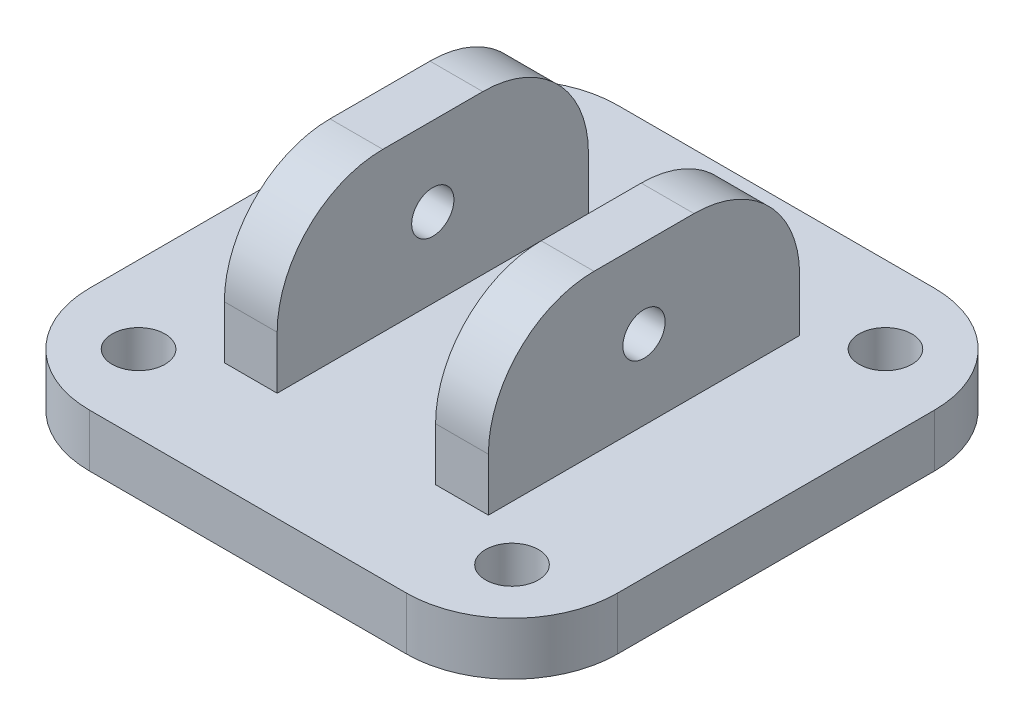
SolidWorks part; units mm, degrees
ref_plane "Front Plane" through (0, 0, 0) normal (0, 0, 1) x (1, 0, 0)
ref_plane "Top Plane" through (0, 0, 0) normal (0, 1, 0) x (1, 0, 0)
ref_plane "Right Plane" through (0, 0, 0) normal (1, 0, 0) x (0, 0, -1)
sketch "Sketch1" plane through (0, 0, 0) normal (0, 1, 0) x (1, 0, 0)
  line L0 (0, 0) -> (-17.68, 0) construction
  line L1 (-17.68, -17.68) -> (17.68, -17.68) construction
  line L2 (-17.68, -17.68) -> (-17.68, 17.68) construction
  line L3 (-17.68, 17.68) -> (17.68, 17.68) construction
  line L4 (17.68, -17.68) -> (17.68, 17.68) construction
  line L5 (-17.68, -17.68) -> (17.68, 17.68) construction
  line L6 (-17.68, 17.68) -> (17.68, -17.68) construction
  line L8 (-25, -25) -> (25, -25)
  line L9 (-25, -25) -> (-25, 25)
  line L10 (-25, 25) -> (25, 25)
  line L11 (25, -25) -> (25, 25)
  line L12 (-25, -25) -> (25, 25) construction
  line L13 (-25, 25) -> (25, -25) construction
  circle A0 centre (-17.68, 17.68) radius 2.5
  circle A1 centre (17.68, 17.68) radius 2.5
  circle A2 centre (17.68, -17.68) radius 2.5
  circle A3 centre (-17.68, -17.68) radius 2.5
  point P0 (0, 0)
  dimension "D3" = 5
  dimension "D4" = 5
  dimension "D1" = 35.36
  dimension "D2" = 35.36
  dimension "D5" = 50
  dimension "D6" = 50
extrude "Boss-Extrude1" add sketch "Sketch1" along normal blind 5
sketch "Sketch2" plane through (0, 5, 0) normal (0, 1, 0) x (1, 0, 0)
  line L1 (-12.5, -14.7343) -> (12.5, -14.7343)
  line L2 (-12.5, -14.7343) -> (-12.5, 14.7343)
  line L3 (-12.5, 14.7343) -> (12.5, 14.7343)
  line L4 (12.5, -14.7343) -> (12.5, 14.7343)
  line L5 (-12.5, -14.7343) -> (12.5, 14.7343) construction
  line L6 (-12.5, 14.7343) -> (12.5, -14.7343) construction
  line L7 (-7.5, -14.7343) -> (7.5, -14.7343)
  line L8 (-7.5, -14.7343) -> (-7.5, 14.7343)
  line L9 (-7.5, 14.7343) -> (7.5, 14.7343)
  line L10 (7.5, -14.7343) -> (7.5, 14.7343)
  line L11 (-7.5, -14.7343) -> (7.5, 14.7343) construction
  line L12 (-7.5, 14.7343) -> (7.5, -14.7343) construction
  point P0 (0, 0)
  point P6 (0, 0)
  dimension "D1" = 25
  dimension "D2" = 15
extrude "Boss-Extrude2" add sketch "Sketch2" along normal blind 15 contours L1 L8 L3 L2 | L10 L1 L4 L3
sketch "Sketch3" plane through (12.5, 0, 0) normal (1, 0, 0) x (0, 0, -1)
  line L0 (0, 20) -> (0, 12.5) construction
  line L1 (-14.7343, 20) -> (14.7343, 20) construction
  circle A0 centre (0, 12.5) radius 2
  dimension "D2" = 4
  dimension "D1" = 7.5
extrude "Cut-Extrude1" cut sketch "Sketch3" against normal through all
fillet "Fillet1" radius 10 4 edges at (10, 20, -14.7343) (10, 20, 14.7343) (-10, 20, 14.7343) (-10, 20, -14.7343)
fillet "Fillet2" radius 10 4 edges at (-25, 2.5, -25) (25, 2.5, -25) (25, 2.5, 25) (-25, 2.5, 25)
